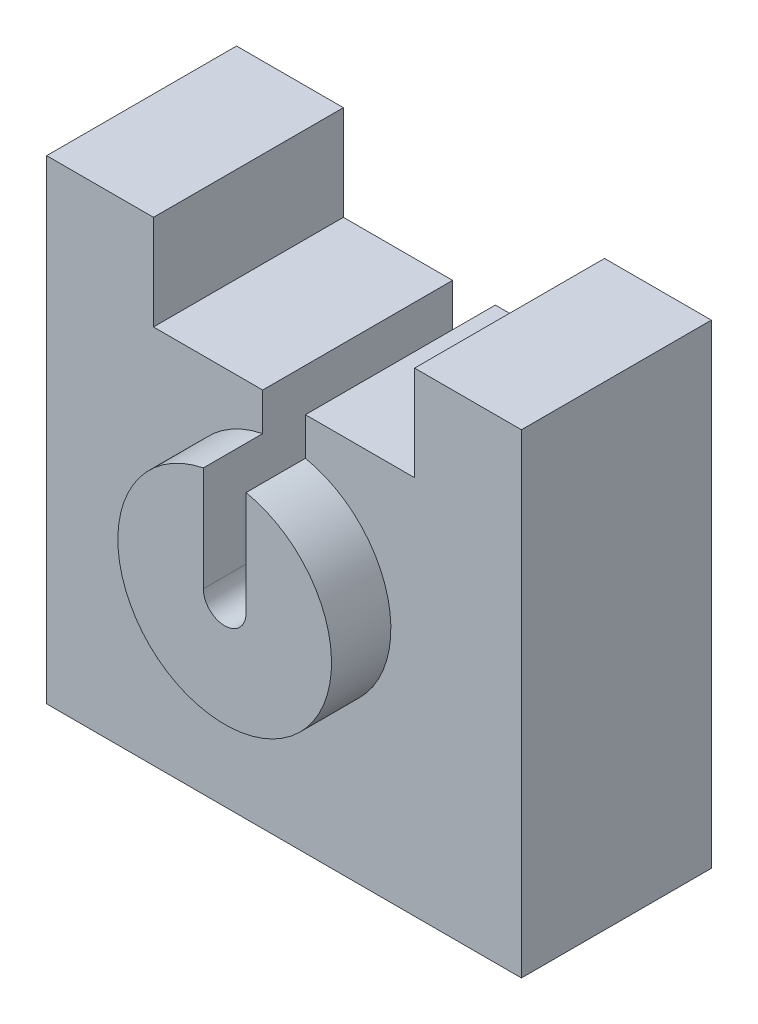
SolidWorks part; units mm, degrees
ref_plane "Front Plane" through (0, 0, 0) normal (0, 0, 1) x (1, 0, 0)
ref_plane "Top Plane" through (0, 0, 0) normal (0, 1, 0) x (1, 0, 0)
ref_plane "Right Plane" through (0, 0, 0) normal (1, 0, 0) x (0, 0, -1)
sketch "Sketch1" plane through (0, 0, 0) normal (0, 0, 1) x (1, 0, 0)
  line L0 (0.275, 0.5) -> (0.5, 0.5)
  line L1 (-0.5, -0.5) -> (0.5, -0.5)
  line L2 (-0.5, -0.5) -> (-0.5, 0.5)
  line L3 (-0.5, 0.5) -> (-0.275, 0.5)
  line L4 (0.5, -0.5) -> (0.5, 0.5)
  line L5 (-0.5, -0.5) -> (0.5, 0.5) construction
  line L6 (-0.5, 0.5) -> (0.5, -0.5) construction
  line L8 (0.275, 0.5) -> (0.275, 0.3)
  line L9 (0.275, 0.3) -> (-0.275, 0.3)
  line L10 (-0.275, 0.5) -> (-0.275, 0.3)
  point P0 (0, 0)
  dimension "D1" = 1
  dimension "D2" = 1
  dimension "D3" = 0.2
  dimension "D4" = 0.55
  dimension "D5" = 0.225
extrude "Boss-Extrude1" add sketch "Sketch1" along normal blind 0.4
sketch "Sketch2" plane through (0, 0, 0) normal (0, 0, -1) x (-1, 0, 0)
  circle A0 centre (0, 0) radius 0.225
extrude "Boss-Extrude2" add sketch "Sketch2" against normal blind 0.525
sketch "Sketch3" plane through (0, 0, 0) normal (0, 0, 1) x (1, 0, 0)
  circle A0 centre (0, 0) radius 0.045
extrude "Cut-Extrude1" cut sketch "Sketch3" along normal through all
sketch "Sketch5" plane through (0, 0, 0) normal (0, 0, -1) x (-1, 0, 0)
  line L0 (0.275, 0.5) -> (0.5, 0.5) construction
  line L1 (0.045, 0) -> (-0.045, 0)
  line L2 (0.045, 0) -> (0.045, 0.5)
  line L3 (0.045, 0.5) -> (-0.045, 0.5)
  line L4 (-0.045, 0) -> (-0.045, 0.5)
  circle A0 centre (0, 0) radius 0.045 construction
extrude "Cut-Extrude2" cut sketch "Sketch5" against normal through all
